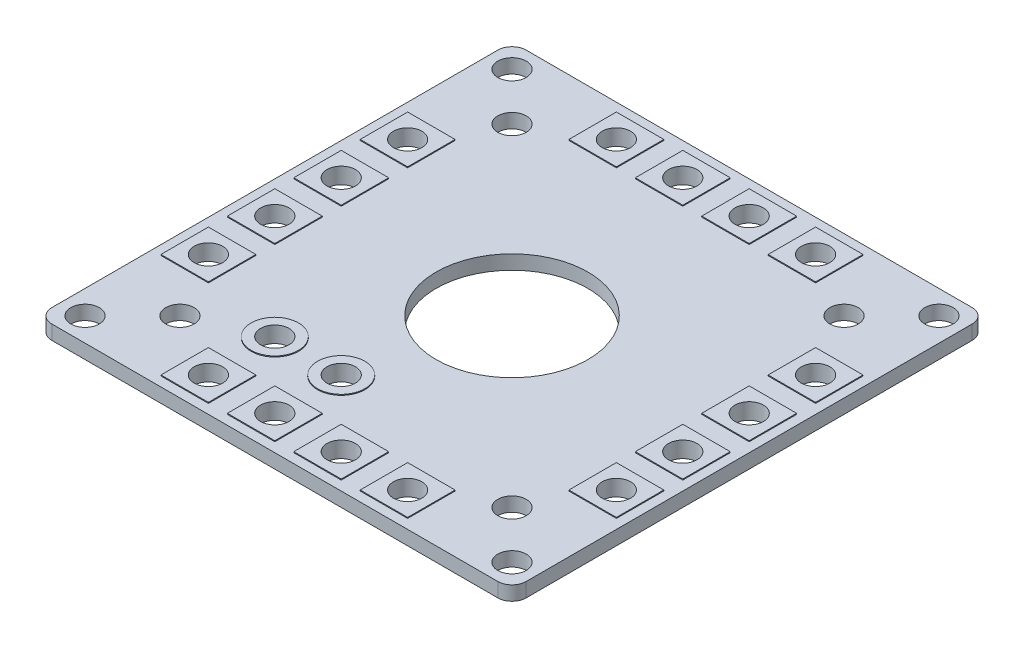
SolidWorks part; units mm, degrees
ref_plane "Спереди" through (0, 0, 0) normal (0, 0, 1) x (1, 0, 0)
ref_plane "Сверху" through (0, 0, 0) normal (0, 1, 0) x (1, 0, 0)
ref_plane "Справа" through (0, 0, 0) normal (1, 0, 0) x (0, 0, -1)
sketch "Эскиз1" plane through (0, 0, 0) normal (0, 1, 0) x (1, 0, 0)
  line L1 (-23.5, 25) -> (23.5, 25)
  line L2 (-25, 23.5) -> (-25, -23.5)
  line L3 (-23.5, -25) -> (23.5, -25)
  line L4 (25, 23.5) -> (25, -23.5)
  line L5 (-25, 25) -> (25, -25) construction
  line L6 (-25, -25) -> (25, 25) construction
  line L7 (-22.5, 22.5) -> (22.5, 22.5) construction
  line L8 (-22.5, 22.5) -> (-22.5, -22.5) construction
  line L9 (-22.5, -22.5) -> (22.5, -22.5) construction
  line L10 (22.5, 22.5) -> (22.5, -22.5) construction
  line L11 (-22.5, 22.5) -> (22.5, -22.5) construction
  line L12 (-22.5, -22.5) -> (22.5, 22.5) construction
  line L13 (-17.5, 17.5) -> (17.5, 17.5) construction
  line L14 (-17.5, 17.5) -> (-17.5, -17.5) construction
  line L15 (-17.5, -17.5) -> (17.5, -17.5) construction
  line L16 (17.5, 17.5) -> (17.5, -17.5) construction
  line L17 (-17.5, 17.5) -> (17.5, -17.5) construction
  line L18 (-17.5, -17.5) -> (17.5, 17.5) construction
  circle A0 centre (-22.5, 22.5) radius 1.5
  circle A1 centre (22.5, 22.5) radius 1.5
  circle A2 centre (22.5, -22.5) radius 1.5
  circle A3 centre (-22.5, -22.5) radius 1.5
  arc A4 (-25, -23.5) -> (-23.5, -25) centre (-23.5, -23.5) ccw
  arc A5 (23.5, -25) -> (25, -23.5) centre (23.5, -23.5) ccw
  arc A6 (23.5, 25) -> (25, 23.5) centre (23.5, 23.5) cw
  arc A7 (-23.5, 25) -> (-25, 23.5) centre (-23.5, 23.5) ccw
  circle A8 centre (-17.5, 17.5) radius 1.5
  circle A9 centre (17.5, 17.5) radius 1.5
  circle A10 centre (17.5, -17.5) radius 1.5
  circle A11 centre (-17.5, -17.5) radius 1.5
  point P0 (0, 0)
  point P6 (0, 0)
  point P27 (0, 0)
  dimension "D5" = 3
  dimension "D6" = 3
  dimension "D7" = 3
  dimension "D8" = 3
  dimension "D9" = 1.5
  dimension "D12" = 3
  dimension "D13" = 3
  dimension "D14" = 3
  dimension "D15" = 3
  dimension "D1" = 50
  dimension "D2" = 50
  dimension "D3" = 45
  dimension "D4" = 45
  dimension "D10" = 35
  dimension "D11" = 35
extrude "Бобышка-Вытянуть1" add sketch "Эскиз1" along normal blind 1.5
sketch "Эскиз2" plane through (0, 1.5, 0) normal (0, 1, 0) x (1, 0, 0)
  line L0 (0, 0) -> (0, 25) construction
  line L1 (23.5, 25) -> (-23.5, 25) construction
  line L3 (1, 24) -> (6, 24)
  line L4 (1, 24) -> (1, 19)
  line L5 (1, 19) -> (6, 19)
  line L6 (6, 24) -> (6, 19)
  line L7 (1, 24) -> (6, 19) construction
  line L8 (1, 19) -> (6, 24) construction
  line L13 (8, 24) -> (13, 19) construction
  line L14 (8, 19) -> (13, 24) construction
  line L18 (-1, 19) -> (-6, 19)
  line L19 (-6, 24) -> (-6, 19)
  line L20 (-1, 24) -> (-6, 24)
  line L21 (-1, 24) -> (-1, 19)
  line L22 (-0.825, 0) -> (0.825, 0) construction
  line L23 (8, -19) -> (13, -19)
  line L24 (13, -24) -> (13, -19)
  line L25 (8, -24) -> (13, -24)
  line L26 (8, -24) -> (8, -19)
  line L27 (1, -19) -> (6, -19)
  line L28 (6, -24) -> (6, -19)
  line L29 (1, -24) -> (6, -24)
  line L30 (1, -24) -> (1, -19)
  line L31 (-1, -24) -> (-1, -19)
  line L32 (-1, -24) -> (-6, -24)
  line L33 (-6, -24) -> (-6, -19)
  line L34 (-1, -19) -> (-6, -19)
  line L35 (-8, -24) -> (-8, -19)
  line L36 (-8, -24) -> (-13, -24)
  line L37 (-13, -24) -> (-13, -19)
  line L38 (-8, -19) -> (-13, -19)
  line L39 (19, 8) -> (19, 13)
  line L40 (24, 13) -> (19, 13)
  line L41 (24, 8) -> (24, 13)
  line L42 (24, 8) -> (19, 8)
  line L43 (19, 1) -> (19, 6)
  line L44 (24, 6) -> (19, 6)
  line L45 (24, 1) -> (24, 6)
  line L46 (24, 1) -> (19, 1)
  line L47 (24, -1) -> (19, -1)
  line L48 (24, -1) -> (24, -6)
  line L49 (24, -6) -> (19, -6)
  line L50 (19, -1) -> (19, -6)
  line L51 (24, -8) -> (19, -8)
  line L52 (24, -8) -> (24, -13)
  line L53 (24, -13) -> (19, -13)
  line L54 (19, -8) -> (19, -13)
  line L55 (-24, 8) -> (-19, 8)
  line L56 (-19, 8) -> (-19, 13)
  line L57 (-24, 13) -> (-19, 13)
  line L58 (-24, 8) -> (-24, 13)
  line L59 (-24, 1) -> (-19, 1)
  line L60 (-19, 1) -> (-19, 6)
  line L61 (-24, 6) -> (-19, 6)
  line L62 (-24, 1) -> (-24, 6)
  line L63 (-19, -1) -> (-19, -6)
  line L64 (-24, -6) -> (-19, -6)
  line L65 (-24, -1) -> (-24, -6)
  line L66 (-24, -1) -> (-19, -1)
  line L67 (-19, -8) -> (-19, -13)
  line L68 (-24, -13) -> (-19, -13)
  line L69 (-24, -8) -> (-24, -13)
  line L70 (-24, -8) -> (-19, -8)
  line L71 (8, -19) -> (13, -19)
  line L72 (13, -24) -> (13, -19)
  line L73 (8, -24) -> (13, -24)
  line L74 (8, -24) -> (8, -19)
  line L75 (1, -19) -> (6, -19)
  line L76 (6, -24) -> (6, -19)
  line L77 (1, -24) -> (6, -24)
  line L78 (1, -24) -> (1, -19)
  line L79 (-1, -24) -> (-1, -19)
  line L80 (-1, -24) -> (-6, -24)
  line L81 (-6, -24) -> (-6, -19)
  line L82 (-1, -19) -> (-6, -19)
  line L83 (-8, -24) -> (-8, -19)
  line L84 (-8, -24) -> (-13, -24)
  line L85 (-13, -24) -> (-13, -19)
  line L86 (-8, -19) -> (-13, -19)
  line L87 (8, 24) -> (8, 19)
  line L88 (8, 19) -> (13, 19)
  line L89 (13, 24) -> (13, 19)
  line L90 (8, 24) -> (13, 24)
  line L99 (-8, 19) -> (-13, 19)
  line L100 (-13, 24) -> (-13, 19)
  line L101 (-8, 24) -> (-13, 24)
  line L102 (-8, 24) -> (-8, 19)
  line L103 (-19, -8) -> (-19, -13)
  line L104 (-24, -13) -> (-19, -13)
  line L105 (-24, -8) -> (-24, -13)
  line L106 (-24, -8) -> (-19, -8)
  line L107 (-19, -1) -> (-19, -6)
  line L108 (-24, -6) -> (-19, -6)
  line L109 (-24, -1) -> (-24, -6)
  line L110 (-24, -1) -> (-19, -1)
  line L111 (-24, 1) -> (-19, 1)
  line L112 (-24, 1) -> (-24, 6)
  line L113 (-24, 6) -> (-19, 6)
  line L114 (-19, 1) -> (-19, 6)
  line L115 (-24, 8) -> (-19, 8)
  line L116 (-24, 8) -> (-24, 13)
  line L117 (-24, 13) -> (-19, 13)
  line L118 (-19, 8) -> (-19, 13)
  line L119 (24, -8) -> (19, -8)
  line L120 (19, -8) -> (19, -13)
  line L121 (24, -13) -> (19, -13)
  line L122 (24, -8) -> (24, -13)
  line L123 (24, -1) -> (19, -1)
  line L124 (19, -1) -> (19, -6)
  line L125 (24, -6) -> (19, -6)
  line L126 (24, -1) -> (24, -6)
  line L127 (19, 1) -> (19, 6)
  line L128 (24, 6) -> (19, 6)
  line L129 (24, 1) -> (24, 6)
  line L130 (24, 1) -> (19, 1)
  line L131 (19, 8) -> (19, 13)
  line L132 (24, 13) -> (19, 13)
  line L133 (24, 8) -> (24, 13)
  line L134 (24, 8) -> (19, 8)
  line L135 (-1, 19) -> (-6, 19) [skipped]
  line L136 (-6, 24) -> (-6, 19) [skipped]
  line L137 (-1, 24) -> (-6, 24) [skipped]
  line L138 (-1, 24) -> (-1, 19) [skipped]
  line L139 (1, 24) -> (1, 19) [skipped]
  line L140 (1, 19) -> (6, 19) [skipped]
  line L141 (6, 24) -> (6, 19) [skipped]
  line L142 (1, 24) -> (6, 24) [skipped]
  line L143 (-25, 23.5) -> (-25, -23.5) construction
  circle A0 centre (0, 0) radius 8
  circle A9 centre (0, 0) radius 8
  circle A10 centre (0, 0) radius 8
  circle A11 centre (0, 0) radius 8
  circle A12 centre (-10.5, -14.5) radius 2.5
  circle A13 centre (-3.5, -14.5) radius 2.5
  point P3 (3.5, 21.5)
  point P11 (10.5, 21.5)
  point P24 (-10.5, -19)
  point P143 (0, 0)
  dimension "D1" = 16
  dimension "D4" = 4
  dimension "D11" = 1
  dimension "D13" = 5
  dimension "D16" = 5
  dimension "D2" = 5
  dimension "D3" = 5
  dimension "D5" = 1
  dimension "D6" = 1
  dimension "D7" = 5
  dimension "D8" = 5
  dimension "D9" = 2
  dimension "D10" = 90
  dimension "D12" = 90
  dimension "D14" = 4.5
  dimension "D15" = 14.5
  dimension "D17" = 4.5
  dimension "D18" = 7
extrude "Вырез-Вытянуть1" cut sketch "Эскиз2" against normal through all contours A0 | L102 L101 L100 L99 | L58 L55 L56 L57 | L62 L59 L60 L61 | L66 L65 L64 L63 | L70 L69 L68 L67 | L35 L38 L37 L36 | L31 L34 L33 L32 | L30 L29 L28 L27 | L26 L25 L24 L23 | L51 L54 L53 L52 | L47 L50 L49 L48 | L46 L45 L44 L43 | L42 L41 L40 L39 | L21 L20 L19 L18 | L88 L89 L90 L87 | L5 L6 L3 L4 | A12 | A13
sketch "Эскиз3" plane through (0, 0, 0) normal (0, 1, 0) x (1, 0, 0)
  line L1 (-13, 24) -> (-8, 24)
  line L2 (-13, 24) -> (-13, 19)
  line L3 (-13, 19) -> (-8, 19)
  line L4 (-8, 24) -> (-8, 19)
  line L5 (-6, 24) -> (-1, 24)
  line L6 (-6, 24) -> (-6, 19)
  line L7 (-6, 19) -> (-1, 19)
  line L8 (-1, 24) -> (-1, 19)
  line L9 (1, 24) -> (6, 24)
  line L10 (1, 24) -> (1, 19)
  line L11 (1, 19) -> (6, 19)
  line L12 (6, 24) -> (6, 19)
  line L13 (8, 24) -> (13, 24)
  line L14 (8, 24) -> (8, 19)
  line L15 (8, 19) -> (13, 19)
  line L16 (13, 24) -> (13, 19)
  line L17 (-24, 13) -> (-19, 13)
  line L18 (-24, 13) -> (-24, 8)
  line L19 (-24, 8) -> (-19, 8)
  line L20 (-19, 13) -> (-19, 8)
  line L21 (-24, 6) -> (-19, 6)
  line L22 (-24, 6) -> (-24, 1)
  line L23 (-24, 1) -> (-19, 1)
  line L24 (-19, 6) -> (-19, 1)
  line L25 (-24, -1) -> (-19, -1)
  line L26 (-24, -1) -> (-24, -6)
  line L27 (-24, -6) -> (-19, -6)
  line L28 (-19, -1) -> (-19, -6)
  line L29 (-24, -8) -> (-19, -8)
  line L30 (-24, -8) -> (-24, -13)
  line L31 (-24, -13) -> (-19, -13)
  line L32 (-19, -8) -> (-19, -13)
  line L33 (-13, -19) -> (-8, -19)
  line L34 (-13, -19) -> (-13, -24)
  line L35 (-13, -24) -> (-8, -24)
  line L36 (-8, -19) -> (-8, -24)
  line L37 (-6, -19) -> (-1, -19)
  line L38 (-6, -19) -> (-6, -24)
  line L39 (-6, -24) -> (-1, -24)
  line L40 (-1, -19) -> (-1, -24)
  line L41 (1, -19) -> (6, -19)
  line L42 (1, -19) -> (1, -24)
  line L43 (1, -24) -> (6, -24)
  line L44 (6, -19) -> (6, -24)
  line L45 (8, -19) -> (13, -19)
  line L46 (8, -19) -> (8, -24)
  line L47 (8, -24) -> (13, -24)
  line L48 (13, -19) -> (13, -24)
  line L49 (19, -8) -> (24, -8)
  line L50 (19, -8) -> (19, -13)
  line L51 (19, -13) -> (24, -13)
  line L52 (24, -8) -> (24, -13)
  line L53 (19, -1) -> (24, -1)
  line L54 (19, -1) -> (19, -6)
  line L55 (19, -6) -> (24, -6)
  line L56 (24, -1) -> (24, -6)
  line L57 (19, 6) -> (24, 6)
  line L58 (19, 6) -> (19, 1)
  line L59 (19, 1) -> (24, 1)
  line L60 (24, 6) -> (24, 1)
  line L61 (19, 13) -> (24, 13)
  line L62 (19, 13) -> (19, 8)
  line L63 (19, 8) -> (24, 8)
  line L64 (24, 13) -> (24, 8)
  circle A0 centre (-10.5, 21.5) radius 1.5
  circle A1 centre (-3.5, 21.5) radius 1.5
  circle A2 centre (3.5, 21.5) radius 1.5
  circle A3 centre (10.5, 21.5) radius 1.5
  circle A4 centre (21.5, 10.5) radius 1.5
  circle A5 centre (21.5, 3.5) radius 1.5
  circle A6 centre (21.5, -3.5) radius 1.5
  circle A7 centre (21.5, -10.5) radius 1.5
  circle A8 centre (10.5, -21.5) radius 1.5
  circle A9 centre (3.5, -21.5) radius 1.5
  circle A10 centre (-3.5, -21.5) radius 1.5
  circle A11 centre (-10.5, -21.5) radius 1.5
  circle A12 centre (-21.5, -10.5) radius 1.5
  circle A13 centre (-21.5, -3.5) radius 1.5
  circle A14 centre (-21.5, 3.5) radius 1.5
  circle A15 centre (-21.5, 10.5) radius 1.5
  circle A16 centre (-10.5, -14.5) radius 2.5
  circle A17 centre (-3.5, -14.5) radius 2.5
  circle A18 centre (-10.5, -14.5) radius 1.5
  circle A19 centre (-3.5, -14.5) radius 1.5
  point P131 (0, 0)
  dimension "D1" = 3
  dimension "D4" = 3
  dimension "D7" = 3
  dimension "D10" = 3
  dimension "D14" = 21.5
  dimension "D16" = 3
  dimension "D17" = 3
  dimension "D2" = 2.5
  dimension "D3" = 2.5
  dimension "D5" = 2.5
  dimension "D6" = 2.5
  dimension "D8" = 2.5
  dimension "D9" = 2.5
  dimension "D11" = 2.5
  dimension "D12" = 2.5
  dimension "D15" = 2.5
  dimension "D13" = 4
extrude "Бобышка-Вытянуть2" add sketch "Эскиз3" along normal blind 1.6 and the other way blind 0.1
